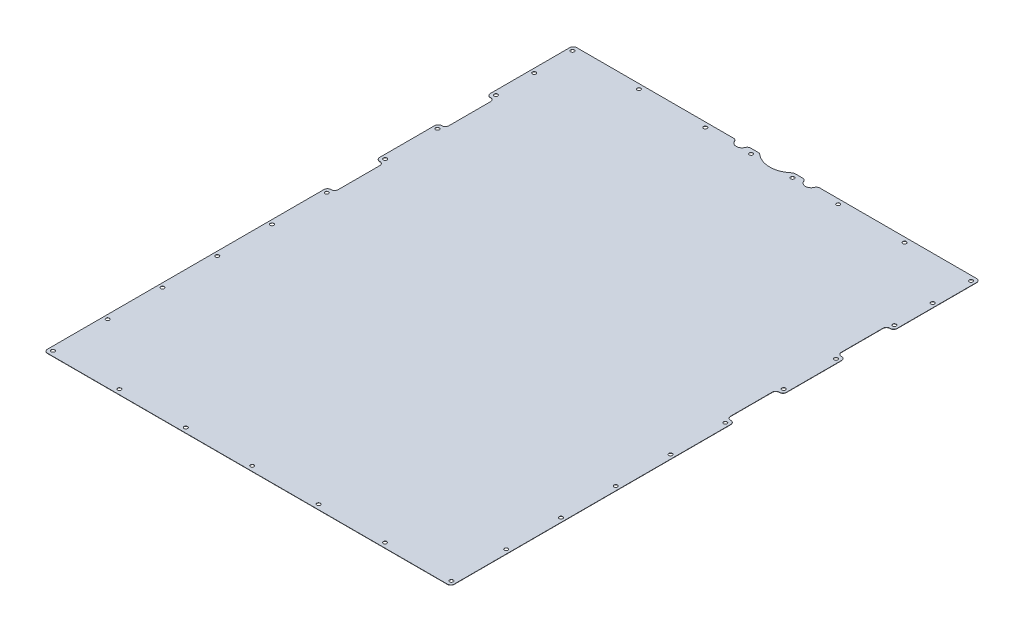
SolidWorks part; units mm, degrees
material "PE High Density Film"
ref_plane "Front Plane" through (0, 0, 0) normal (0, 0, 1) x (1, 0, 0)
ref_plane "Top Plane" through (0, 0, 0) normal (0, 1, 0) x (1, 0, 0)
ref_plane "Right Plane" through (0, 0, 0) normal (1, 0, 0) x (0, 0, -1)
sketch "Sketch1" plane through (0, 0, 0) normal (0, 1, 0) x (1, 0, 0)
  line L1 (-186.69, -242.8875) -> (186.69, -242.8875)
  line L2 (-186.69, -242.8875) -> (-186.69, 242.8875)
  line L3 (-186.69, 242.8875) -> (186.69, 242.8875)
  line L4 (186.69, -242.8875) -> (186.69, 242.8875)
  line L5 (-186.69, -242.8875) -> (186.69, 242.8875) construction
  line L6 (-186.69, 242.8875) -> (186.69, -242.8875) construction
  point P0 (0, 0)
  dimension "D1" = 485.775
  dimension "D2" = 373.38
extrude "Boss-Extrude1" add sketch "Sketch1" along normal blind 0.254
sketch "Sketch2" plane through (0, 0.254, 0) normal (0, 1, 0) x (1, 0, 0)
  line L0 (186.69, 242.8875) -> (-186.69, 242.8875) construction
  line L1 (-186.69, 163.6395) -> (-180.086, 163.6395)
  line L2 (-186.69, 163.6395) -> (-186.69, 118.9355)
  line L3 (-186.69, 118.9355) -> (-180.086, 118.9355)
  line L4 (-180.086, 163.6395) -> (-180.086, 118.9355)
  line L5 (-186.69, 242.8875) -> (-186.69, -242.8875) construction
  line L7 (-180.086, 17.3355) -> (-186.69, 17.3355)
  line L8 (-180.086, 17.3355) -> (-180.086, 62.0395)
  line L9 (-180.086, 62.0395) -> (-186.69, 62.0395)
  line L10 (-186.69, 17.3355) -> (-186.69, 62.0395)
  line L11 (-186.69, 141.2875) -> (-180.086, 141.2875) construction
  line L12 (-186.69, 39.6875) -> (-180.086, 39.6875) construction
  dimension "D1" = 79.248
  dimension "D2" = 44.704
  dimension "D3" = 6.604
  dimension "D4" = 101.6
  dimension "D5" = 44.704
extrude "Cut-Extrude1" cut sketch "Sketch2" against normal through all
mirror "Mirror1" about plane through (0, 0, 0) normal (1, 0, 0) of "Cut-Extrude1"
fillet "Fillet1" radius 3.175 20 edges at (-180.086, 0.127, -118.9355) (-180.086, 0.127, -163.6395) (186.69, 0.127, -242.8875) (186.69, 0.127, -163.6395) (180.086, 0.127, -163.6395) (180.086, 0.127, -118.9355) (186.69, 0.127, -118.9355) (186.69, 0.127, -62.0395) (180.086, 0.127, -62.0395) (180.086, 0.127, -17.3355) (186.69, 0.127, -17.3355) (186.69, 0.127, 242.8875) (-186.69, 0.127, 242.8875) (-186.69, 0.127, -242.8875) (-186.69, 0.127, -118.9355) (-186.69, 0.127, -163.6395) (-186.69, 0.127, -17.3355) (-186.69, 0.127, -62.0395) (-180.086, 0.127, -17.3355) (-180.086, 0.127, -62.0395)
hole_wizard "#4 Clearance Hole1" positions "Sketch4" profile "Sketch3" hole size "#4" standard "Ansi Inch"
sketch "Sketch4" plane through (0, 0.254, 0) normal (0, 1, 0) x (-1, 0, 0)
  line L0 (186.69, -239.7125) -> (186.69, -166.8145) construction
  line L1 (-183.515, -242.8875) -> (183.515, -242.8875) construction
  line L2 (183.261, -163.6395) -> (183.515, -163.6395) construction
  point P0 (182.88, -238.4425)
  point P7 (182.88, -168.0845)
  point P13 (182.88, -203.2635)
  point P16 (182.88, -114.4905)
  point P18 (182.88, -66.4845)
  point P22 (182.88, -12.8905)
  point P37 (182.88, 37.3761)
  point P38 (182.88, 87.6427)
  point P39 (182.88, 137.9093)
  point P40 (182.88, 188.1759)
  point P41 (182.88, 238.4425)
  point P44 (182.88, 288.7091) [skipped]
  dimension "D1" = 3.81
  dimension "D2" = 4.445
  dimension "D3" = 4.445
  dimension "D4" = 35.179
  dimension "D5" = 4.445
  dimension "D6" = 4.445
  dimension "D8" = 4.445
  dimension "D12" = 50.2666
  dimension "D11" = 7
sketch "Sketch3" plane through (-182.88, 0.254, -238.4425) normal (1, 0, 0) x (0, 0, 1)
  line L0 (0, 0) -> (0, 1.7426)
  line L1 (0, 1.7426) -> (1.6319, 0.762)
  line L2 (1.6319, 0.762) -> (1.6319, 0)
  line L5 (1.6319, 0) -> (0, 0)
  line L10 (0, 1.7426) -> (-1.6319, 0.762) construction
  line L11 (0, -6.35) -> (0, 107.95) construction
  dimension "Hole Dia." = 3.2639
  dimension "Hole Depth" = 0.762
  dimension "Drill Angle" = 118
mirror "Mirror2" about plane through (0, 0, 0) normal (1, 0, 0) of "#4 Clearance Hole1"
hole_wizard "#4 Clearance Hole2" positions "Sketch6" profile "Sketch5" hole size "#4" standard "Ansi Inch"
sketch "Sketch6" plane through (0, 0.254, 0) normal (0, 1, 0) x (-1, 0, 0)
  line L0 (-183.515, -242.8875) -> (183.515, -242.8875) construction
  circle A1 centre (182.88, -238.4425) radius 1.6319 construction
  point P0 (121.92, -238.4425)
  point P15 (60.96, -238.4425)
  point P16 (0, -238.4425)
  point P17 (-60.96, -238.4425)
  point P18 (-121.92, -238.4425)
  dimension "D1" = 4.445
  dimension "D2" = 60.96
  dimension "D3" = 5
sketch "Sketch5" plane through (-121.92, 0.254, -238.4425) normal (1, 0, 0) x (0, 0, 1)
  line L0 (0, 0) -> (0, 1.7426)
  line L1 (0, 1.7426) -> (1.6319, 0.762)
  line L2 (1.6319, 0.762) -> (1.6319, 0)
  line L5 (1.6319, 0) -> (0, 0)
  line L10 (0, 1.7426) -> (-1.6319, 0.762) construction
  line L11 (0, -6.35) -> (0, 107.95) construction
  dimension "Hole Dia." = 3.2639
  dimension "Hole Depth" = 0.762
  dimension "Drill Angle" = 118
mirror "Mirror3" about plane through (0, 0, 0) normal (0, 0, 1) of "#4 Clearance Hole2"
sketch "Sketch7" plane through (0, 0.254, 0) normal (0, 1, 0) x (1, 0, 0)
  line L0 (183.515, 242.8875) -> (-183.515, 242.8875) construction
  circle A0 centre (0, 258.7625) radius 22.225
  dimension "D2" = 44.45
  dimension "D1" = 15.875
extrude "Cut-Extrude2" cut sketch "Sketch7" against normal up to next
fillet "Fillet2" radius 3.175 2 edges at (15.5543, 0.127, -242.8875) (-15.5543, 0.127, -242.8875)
hole_wizard "#4 Clearance Hole3" positions "Sketch9" profile "Sketch8" hole size "#4" standard "Ansi Inch" end condition up to next
sketch "Sketch9" plane through (0, 0.254, 0) normal (0, 1, 0) x (-1, 0, 0)
  line L0 (-183.515, -242.8875) -> (-16.8005, -242.8875) construction
  arc A1 (14.7005, -242.0938) -> (-14.7005, -242.0938) centre (0, -258.7625) ccw construction
  point P0 (19.05, -238.4425)
  point P1 (-19.05, -238.4425)
  point P8 (0, -236.5375)
  dimension "D1" = 4.445
  dimension "D2" = 19.05
  dimension "D3" = 38.1
sketch "Sketch8" plane through (-19.05, 0.254, -238.4425) normal (1, 0, 0) x (0, 0, 1)
  line L0 (0, 0) -> (0, 0.254)
  line L1 (0, 0.254) -> (1.632, 0.254)
  line L2 (1.632, 0.254) -> (1.6319, 0)
  line L5 (1.6319, 0) -> (0, 0)
  line L11 (0, -6.35) -> (0, 107.95) construction
  dimension "Thru Hole Dia." = 3.2639
  dimension "Thru Hole Depth" = 0.254
sketch "Sketch10" plane through (0, 0.254, 0) normal (0, 1, 0) x (1, 0, 0)
  line L0 (183.515, 242.8875) -> (16.8005, 242.8875) construction
  circle A0 centre (31.75, 242.8875) radius 5.334
  circle A1 centre (-31.75, 242.8875) radius 5.334
  dimension "D1" = 10.668
  dimension "D2" = 63.5
  dimension "D3" = 31.75
extrude "Cut-Extrude3" cut sketch "Sketch10" against normal blind 1.016
fillet "Fillet3" radius 3.175 4 edges at (-37.084, 0.127, -242.8875) (-26.416, 0.127, -242.8875) (26.416, 0.127, -242.8875) (37.084, 0.127, -242.8875)
